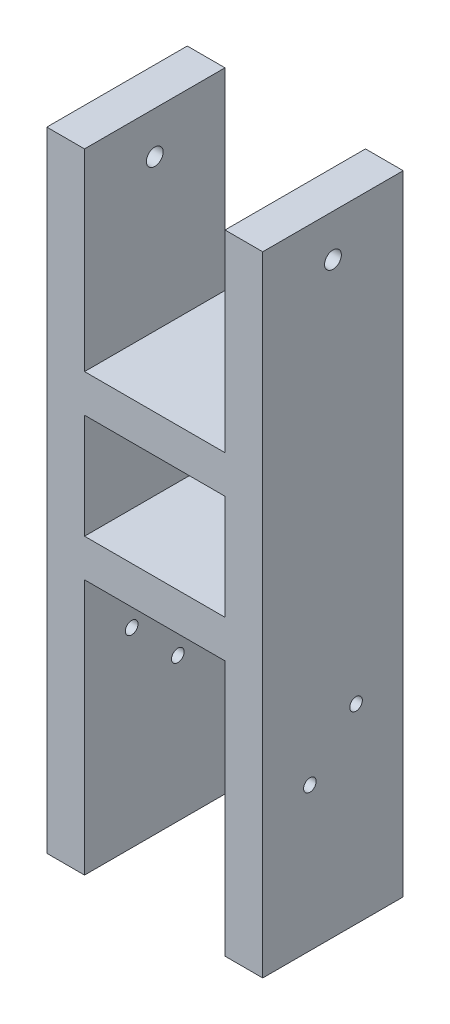
SolidWorks part; units mm, degrees
ref_plane "Front Plane" through (0, 0, 0) normal (0, 0, 1) x (1, 0, 0)
ref_plane "Top Plane" through (0, 0, 0) normal (0, 1, 0) x (1, 0, 0)
ref_plane "Right Plane" through (0, 0, 0) normal (1, 0, 0) x (0, 0, -1)
sketch "Sketch1" plane through (0, 0, 0) normal (0, 0, 1) x (1, 0, 0)
  line L5 (1.3306, 23.6605) -> (1.3306, -98.3395)
  line L6 (1.3306, -98.3395) -> (-16.6694, -98.3395)
  line L7 (-16.6694, -98.3395) -> (-16.6694, 201.6605)
  line L8 (-16.6694, 201.6605) -> (1.3306, 201.6605)
  line L17 (1.3306, 41.6605) -> (68.3306, 41.6605)
  line L19 (68.3306, 23.6605) -> (1.3306, 23.6605)
  line L20 (34.8306, 293.3392) -> (34.8306, -253.3027) construction
  line L21 (1.3306, 41.6605) -> (1.3306, 91.6605)
  line L22 (1.3306, 91.6605) -> (68.3306, 91.6605)
  line L24 (68.3306, 109.6605) -> (1.3306, 109.6605)
  line L25 (1.3306, 109.6605) -> (1.3306, 201.6605)
  line L26 (68.3306, -98.3395) -> (86.3306, -98.3395)
  line L27 (68.3306, 23.6605) -> (68.3306, -98.3395)
  line L28 (68.3306, 41.6605) -> (68.3306, 91.6605)
  line L29 (68.3306, 109.6605) -> (68.3306, 201.6605)
  line L30 (86.3306, 201.6605) -> (68.3306, 201.6605)
  line L31 (86.3306, -98.3395) -> (86.3306, 201.6605)
  point P10 (34.8306, 91.6605)
  dimension "D1" = 300
  dimension "D2" = 18
  dimension "D3" = 122
  dimension "D4" = 140
  dimension "D5" = 18
  dimension "D6" = 50
extrude "Boss-Extrude3" add sketch "Sketch1" along normal blind 67
sketch "Sketch2" plane through (86.3306, 0, 0) normal (1, 0, 0) x (0, 0, -1)
  line L0 (-33.5, 308.3741) -> (-33.5, -164.3808) construction
  line L1 (-67, -98.3395) -> (0, -98.3395) construction
  line L2 (-67, 201.6605) -> (0, 201.6605) construction
  circle A0 centre (-44.5, -29.8395) radius 3
  circle A1 centre (-22.5, -7.3395) radius 3
  circle A2 centre (-33.5, 181.6605) radius 4
  dimension "D1" = 6
  dimension "D2" = 6
  dimension "D7" = 8
  dimension "D3" = 11
  dimension "D4" = 11
  dimension "D5" = 68.5
  dimension "D6" = 91
  dimension "D8" = 20
extrude "Cut-Extrude1" cut sketch "Sketch2" against normal blind 18
sketch "Sketch3" plane through (-16.6694, 0, 0) normal (-1, 0, 0) x (0, 0, 1)
  line L0 (33.5, 278.6397) -> (33.5, -148.0543) construction
  line L1 (67, 201.6605) -> (0, 201.6605) construction
  line L2 (67, -98.3395) -> (0, -98.3395) construction
  line L3 (67, 201.6605) -> (67, -98.3395) construction
  circle A0 centre (22.5, -29.8395) radius 3
  circle A1 centre (44.5, -7.3395) radius 3
  circle A2 centre (33.5, 181.6605) radius 4
  dimension "D1" = 8
  dimension "D3" = 6
  dimension "D4" = 6
  dimension "D2" = 20
  dimension "D5" = 68.5
  dimension "D6" = 91
  dimension "D7" = 11
  dimension "D8" = 11
  dimension "D9" = 33.5
extrude "Cut-Extrude2" cut sketch "Sketch3" against normal blind 18
